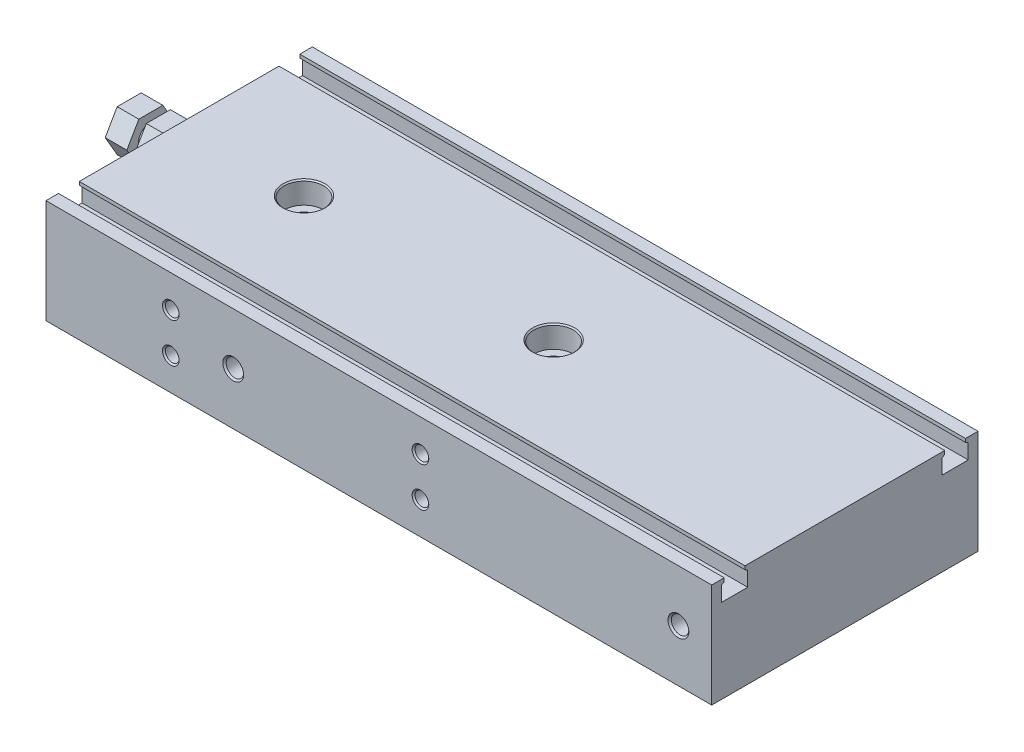
SolidWorks part; units mm, degrees
ref_plane "Plane1" through (0, 0, 0) normal (0, 0, 1) x (1, 0, 0)
ref_plane "Plane2" through (0, 0, 0) normal (0, 1, 0) x (1, 0, 0)
ref_plane "Plane3" through (0, 0, 0) normal (1, 0, 0) x (0, 0, -1)
sketch "Body_Sketch" plane through (0, 0, 0) normal (1, 0, 0) x (0, 0, -1)
  line L0 (-32, 12.5) -> (-32, -12.5)
  line L1 (-32, -12.5) -> (32, -12.5)
  line L2 (32, -12.5) -> (32, 12.5)
  line L3 (32, 12.5) -> (-32, 12.5)
  line L4 (-25.3, 0) -> (25.3, 0) construction
  line L5 (0, -7.85) -> (0, 10.85) construction
  line L6 (27.956, 0) -> (-27.956, 0) construction
  line L7 (0, 12.3416) -> (0, -12.3416) construction
  dimension "A" = 64
  dimension "B" = 25
  dimension "QQ" = 12.5
extrude "Body" add sketch "Body_Sketch" along normal blind 160
sketch "Body Bot Grooves_Sketch" [suppressed] plane through (0, 0, 0) normal (1, 0, 0) x (0, 0, -1)
  line L0 (0, 0) -> (0, -14.4793) construction
  line L1 (-12, -6.5) -> (-4, -6.5)
  line L2 (-4, -6.5) -> (-5, -5.5)
  line L3 (-5, -5.5) -> (-11, -5.5)
  line L4 (-11, -5.5) -> (-12, -6.5)
  line L5 (-8, -5.5) -> (-8, -12.5787) construction
  line L6 (18.5, 10) -> (-18.5, 10) construction
  line L7 (11, -5.5) -> (12, -6.5)
  line L8 (5, -5.5) -> (11, -5.5)
  line L9 (4, -6.5) -> (5, -5.5)
  line L10 (12, -6.5) -> (4, -6.5)
  dimension "Angle" = 45
  dimension "Raw Height" = 16.5
  dimension "Loc Y" = 15.5
  dimension "Width" = 8
  dimension "C2C" = 16
extrude "Body Bot Grooves" [suppressed] cut sketch "Body Bot Grooves_Sketch" along normal through all
sketch "Body Rod Holes_Sketch" plane through (0, 0, 0) normal (-1, 0, 0) x (0, 0, 1)
  line L0 (27.956, 0) -> (-27.956, 0) construction
  line L1 (0, 11.1009) -> (0, -8.2638) construction
  line L2 (0, -12.3416) -> (0, 12.3416) construction
  circle A0 centre (-14, 0) radius 5
  circle A1 centre (14, 0) radius 5
  dimension "NN" = 10
  dimension "H" = 28
extrude "Body Rod Holes" cut sketch "Body Rod Holes_Sketch" against normal blind 10
sketch "Body Piston Holes_Sketch" plane through (10, 0, 0) normal (-1, 0, 0) x (0, 0, 1)
  circle A0 centre (14, 0) radius 6.05
  circle A1 centre (-14, 0) radius 6.05
extrude "Body Piston Holes" cut sketch "Body Piston Holes_Sketch" against normal blind 91
sketch "Body Thru Hole_Sketch" [suppressed] plane through (0, 0, 0) normal (1, 0, 0) x (0, 0, -1)
  line L0 (0, 0) -> (0, -9.4152) construction
  line L1 (11.5, -6) -> (18.5, -6) construction
  circle A0 centre (14.95, -3) radius 1.4
  dimension "Dia" = 2.8
  dimension "Loc Y" = 3
  dimension "Loc Z" = 14.95
extrude "Body Thru Hole" [suppressed] cut sketch "Body Thru Hole_Sketch" along normal through all
sketch "Bot Switch Groove_Sketch" [suppressed] plane through (0, 0, 0) normal (1, 0, 0) x (0, 0, -1)
  line L0 (0, 0) -> (0, -12.0384) construction
  line L1 (1.6, -6.5) -> (-1.6, -6.5)
  line L2 (-1.6, -6.5) -> (-1.6, -3)
  line L3 (-1.6, -3) -> (-2.8, -3)
  line L4 (-2.8, -3) -> (-2.8, 0)
  line L5 (-2.8, 0) -> (2.8, 0)
  line L6 (2.8, -3) -> (2.8, 0)
  line L7 (-12, -6.5) -> (-4, -6.5) construction
  line L8 (1.6, -3) -> (2.8, -3)
  line L10 (1.6, -6.5) -> (1.6, -3)
  point P12 (0, 0)
  point P15 (0, -6.5)
  dimension "Bot Height" = 3.5
  dimension "Top Height" = 3
  dimension "Bot Width" = 3.2
  dimension "Top Width" = 5.6
extrude "Bot Switch Groove" [suppressed] cut sketch "Bot Switch Groove_Sketch" along normal through all
sketch "Top Switch Grooves_Sketch" plane through (0, 0, 0) normal (-1, 0, 0) x (0, 0, 1)
  line L0 (0, -12.3416) -> (0, 12.3416) construction
  line L1 (26.5, 4.6906) -> (26.5, 11.0706) construction
  line L2 (-32, 12.5) -> (32, 12.5) construction
  line L3 (23.35, 7.7) -> (29.65, 7.7)
  line L4 (-23.35, 11.3) -> (-23.35, 7.7)
  line L5 (-23.35, 7.7) -> (-29.65, 7.7)
  line L6 (-29.65, 7.7) -> (-29.65, 11.3)
  line L7 (-29, 12.5) -> (-24, 12.5)
  line L8 (29.65, 7.7) -> (29.65, 11.3)
  line L9 (29, 11.6753) -> (29.65, 11.3)
  line L10 (29, 12.5) -> (29, 11.6753)
  line L11 (29, 12.5) -> (24, 12.5)
  line L12 (-29, 12.5) -> (-29, 11.6753)
  line L13 (-24, 12.5) -> (-24, 11.6753)
  line L14 (-24, 11.6753) -> (-23.35, 11.3)
  line L15 (-29, 11.6753) -> (-29.65, 11.3)
  line L16 (0, 4.91) -> (0, 11.29) construction
  line L17 (24, 12.5) -> (24, 11.6753)
  line L18 (-26.5, 4.91) -> (-26.5, 11.29) construction
  line L19 (24, 11.6753) -> (23.35, 11.3)
  line L20 (23.35, 11.3) -> (23.35, 7.7)
  point P4 (-26.5, 12.5)
  point P12 (26.5, 12.5)
  dimension "Bot Width" = 6.3
  dimension "Top Width" = 5
  dimension "P" = 53
  dimension "Bot Height" = 3.6
  dimension "Angle" = 120
  dimension "Depth" = 4.8
extrude "Top Switch Grooves" cut sketch "Top Switch Grooves_Sketch" against normal through all
sketch "SHCS MGT Hole_Sketch" plane through (0, 0, 0) normal (0, 0, 1) x (1, 0, 0)
  line L0 (30, 12.5) -> (25.25, 12.5)
  line L1 (25.25, 12.5) -> (25.25, 7.2)
  line L2 (25.25, 7.2) -> (27.25, 7.2)
  line L3 (27.25, 7.2) -> (27.25, -12.5)
  line L4 (27.25, -12.5) -> (30, -12.5)
  line L5 (30, -12.5) -> (30, 12.5)
  line L6 (30, -11.5069) -> (30, 12.6548) construction
  line L7 (160, 12.5) -> (0, 12.5) construction
  line L8 (160, -12.5) -> (0, -12.5) construction
  line L9 (0, -12.5712) -> (0, 12.5712) construction
  dimension "M_depth" = 5.3
  dimension "M" = 9.5
  dimension "U" = 5.5
  dimension "L" = 30
revolve "SHCS MGT Hole" cut sketch "SHCS MGT Hole_Sketch" angle 360 about L6
chamfer "SHCS MGT Hole Cham" distance 0.3 1 edges at (30, 12.5, -4.75)
pattern_linear "SHCS MGT Hole Pat" count 2 spacing 60 along (1, 0, 0) of "SHCS MGT Hole", "SHCS MGT Hole Cham"
hole_wizard "SHCS MGT Hole Bot Tap" positions "SHCS MGT Hole Bot Tap Loc" profile "SHCS MGT Hole Bot Tap Profile" tap size "M4x0.7" standard "Ansi Metric"
sketch "SHCS MGT Hole Bot Tap Loc" plane through (0, -12.5, 0) normal (0, -1, 0) x (1, 0, 0)
  circle A0 centre (90, 0) radius 2.75 construction
  circle A1 centre (30, 0) radius 2.75 construction
  point P0 (30, 0)
  point P1 (90, 0)
sketch "SHCS MGT Hole Bot Tap Profile" plane through (30, -12.5, 0) normal (1, 0, 0) x (0, 0, -1)
  line L0 (0, 0) -> (0, 12.6524)
  line L1 (0, 12.6524) -> (2.75, 11)
  line L2 (2.75, 11) -> (2.75, 10)
  line L3 (2.75, 10) -> (3, 10)
  line L5 (3, 10) -> (3, 0.3)
  line L6 (3, 0.3) -> (3.3, 0)
  line L7 (3.3, 0) -> (0, 0)
  line L8 (-3, 0.3) -> (-3.3, 0) construction
  line L10 (0, 12.6524) -> (-2.75, 11) construction
  line L11 (0, -6.35) -> (0, 107.95) construction
  dimension "Tap Drill Dia." = 5.5
  dimension "Tap Drill Depth" = 11
  dimension "Thread Major Dia." = 6
  dimension "Thread Depth" = 10
  dimension "Near CSink Dia." = 6.6
  dimension "Near CSink Angle" = 90
  dimension "Drill Angle" = 118
sketch "Adjuster Nut_Sketch" plane through (0, 0, 0) normal (-1, 0, 0) x (0, 0, 1)
  line L0 (-2.8868, 11.5) -> (2.8868, 11.5)
  line L1 (2.8868, 11.5) -> (5.7735, 6.5)
  line L2 (2.8868, 1.5) -> (5.7735, 6.5)
  line L3 (2.8868, 1.5) -> (-2.8868, 1.5)
  line L4 (-5.7735, 6.5) -> (-2.8868, 1.5)
  line L5 (-2.8868, 11.5) -> (-5.7735, 6.5)
  line L6 (0, -12.3416) -> (0, 12.3416) construction
  line L7 (27.956, 0) -> (-27.956, 0) construction
  line L8 (-4.4456, 6.5) -> (4.4456, 6.5) construction
  line L10 (0, 1.15) -> (0, 8.85) construction
  circle A0 centre (0, 6.5) radius 5 construction
  dimension "OO_keyw" = 10
  dimension "TT" = 6.5
extrude "Adjuster Nut" add sketch "Adjuster Nut_Sketch" along normal blind 12
sketch "Adjuster Nut Threads_Sketch" plane through (0, 0, 0) normal (0, 0, 1) x (1, 0, 0)
  line L0 (-6.8, 34.5) -> (-6.8, 9.5)
  line L1 (-6.8, 9.5) -> (-5, 9.5)
  line L2 (-5, 9.5) -> (-5, 34.5)
  line L3 (-5, 34.5) -> (-6.8, 34.5)
  line L4 (-6.476, 6.5) -> (-3.044, 6.5) construction
  line L5 (-12, 6.5) -> (0, 6.5) construction
  line L6 (0, -12.5712) -> (0, 12.5712) construction
  line L7 (-12, 6.5) -> (-12, 11.5) construction
  line L8 (0, 12.5) -> (0, -12.5) construction
  dimension "OO" = 6
  dimension "Nut Thickness Body" = 5
  dimension "Nut Thickness Plate" = 5.2
revolve "Adjuster Nut Threads" cut sketch "Adjuster Nut Threads_Sketch" angle 360 about L4
hole_wizard "Tap Drill for M5x0.8 Tap1" positions "Sketch2" profile "Sketch1" hole size "M5x0.8" standard "ANSI Metric"
sketch "Sketch2" plane through (0, 0, 32) normal (0, 0, 1) x (1, 0, 0)
  line L0 (160, -12.5) -> (0, -12.5) construction
  line L1 (160, 12.5) -> (160, -12.5) construction
  line L2 (0, 12.5) -> (0, -12.5) construction
  point P0 (45, 0)
  point P2 (152, 0)
  dimension "D1" = 12.5
  dimension "D2" = 8
  dimension "D3" = 45
sketch "Sketch1" plane through (45, 0, 32) normal (1, 0, 0) x (0, -1, 0)
  line L0 (0, 0) -> (0, 5.7618)
  line L1 (0, 5.7618) -> (2.1, 4.5)
  line L2 (2.1, 4.5) -> (2.1, 0.4)
  line L3 (2.1, 0.4) -> (2.5, 0)
  line L5 (2.5, 0) -> (0, 0)
  line L6 (-2.1, 0.4) -> (-2.5, 0) construction
  line L10 (0, 5.7618) -> (-2.1, 4.5) construction
  line L11 (0, -6.35) -> (0, 107.95) construction
  dimension "Hole Dia." = 4.2
  dimension "Hole Depth" = 4.5
  dimension "Near C'Sink Dia." = 5
  dimension "Near C'Sink Angle" = 90
  dimension "Drill Angle" = 118
hole_wizard "Tap Drill for M5x0.8 Tap2" positions "Sketch4" profile "Sketch3" hole size "M5x0.8" standard "ANSI Metric"
sketch "Sketch4" plane through (0, 0, -32) normal (0, 0, -1) x (-1, 0, 0)
  line L0 (-160, -12.5) -> (-160, 12.5) construction
  line L1 (0, -12.5) -> (0, 12.5) construction
  line L2 (-160, -12.5) -> (0, -12.5) construction
  point P0 (-152, 0)
  point P2 (-45, 0)
  dimension "D1" = 8
  dimension "D2" = 45
  dimension "D3" = 12.5
sketch "Sketch3" plane through (152, 0, -32) normal (1, 0, 0) x (0, 1, 0)
  line L0 (0, 0) -> (0, 5.7618)
  line L1 (0, 5.7618) -> (2.1, 4.5)
  line L2 (2.1, 4.5) -> (2.1, 0.4)
  line L3 (2.1, 0.4) -> (2.5, 0)
  line L5 (2.5, 0) -> (0, 0)
  line L6 (-2.1, 0.4) -> (-2.5, 0) construction
  line L10 (0, 5.7618) -> (-2.1, 4.5) construction
  line L11 (0, -6.35) -> (0, 107.95) construction
  dimension "Hole Dia." = 4.2
  dimension "Hole Depth" = 4.5
  dimension "Near C'Sink Dia." = 5
  dimension "Near C'Sink Angle" = 90
  dimension "Drill Angle" = 118
hole_wizard "Mount_Holes_1" positions "Sketch6" profile "Sketch5" hole size "M3x0.5" standard "ANSI Metric"
sketch "Sketch6" plane through (0, 0, 32) normal (0, 0, 1) x (1, 0, 0)
  line L0 (160, -12.5) -> (0, -12.5) construction
  line L1 (0, 12.5) -> (0, -12.5) construction
  point P0 (30, -4.75)
  point P2 (90, -4.75)
  dimension "D1" = 7.75
  dimension "D2" = 30
  dimension "D3" = 60
sketch "Sketch5" plane through (30, -4.75, 32) normal (1, 0, 0) x (0, -1, 0)
  line L0 (0, 0) -> (0, 6.4914)
  line L1 (0, 6.4914) -> (1.65, 5.5)
  line L2 (1.65, 5.5) -> (1.65, 0.35)
  line L3 (1.65, 0.35) -> (2, 0)
  line L5 (2, 0) -> (0, 0)
  line L6 (-1.65, 0.35) -> (-2, 0) construction
  line L10 (0, 6.4914) -> (-1.65, 5.5) construction
  line L11 (0, -6.35) -> (0, 107.95) construction
  dimension "Hole Dia." = 3.3
  dimension "Hole Depth" = 5.5
  dimension "Near C'Sink Dia." = 4
  dimension "Near C'Sink Angle" = 90
  dimension "Drill Angle" = 118
hole_wizard "Mount_Holes_2" positions "Sketch8" profile "Sketch7" hole size "M3x0.5" standard "ANSI Metric"
sketch "Sketch8" plane through (0, 0, -32) normal (0, 0, -1) x (-1, 0, 0)
  line L0 (-160, -12.5) -> (0, -12.5) construction
  line L1 (0, -12.5) -> (0, 12.5) construction
  point P0 (-90, -4.75)
  point P2 (-30, -4.75)
  dimension "D1" = 7.75
  dimension "D2" = 30
  dimension "D3" = 60
sketch "Sketch7" plane through (90, -4.75, -32) normal (1, 0, 0) x (0, 1, 0)
  line L0 (0, 0) -> (0, 6.4914)
  line L1 (0, 6.4914) -> (1.65, 5.5)
  line L2 (1.65, 5.5) -> (1.65, 0.35)
  line L3 (1.65, 0.35) -> (2, 0)
  line L5 (2, 0) -> (0, 0)
  line L6 (-1.65, 0.35) -> (-2, 0) construction
  line L10 (0, 6.4914) -> (-1.65, 5.5) construction
  line L11 (0, -6.35) -> (0, 107.95) construction
  dimension "Hole Dia." = 3.3
  dimension "Hole Depth" = 5.5
  dimension "Near C'Sink Dia." = 4
  dimension "Near C'Sink Angle" = 90
  dimension "Drill Angle" = 118
hole_wizard "Mount_Holes_3" positions "Sketch10" profile "Sketch9" hole size "M4x0.7" standard "ANSI Metric"
sketch "Sketch10" plane through (0, 0, 32) normal (0, 0, 1) x (1, 0, 0)
  line L0 (160, 12.5) -> (0, 12.5) construction
  line L1 (0, 12.5) -> (0, -12.5) construction
  point P0 (30, 4.75)
  point P2 (90, 4.75)
  dimension "D1" = 7.75
  dimension "D2" = 30
  dimension "D3" = 60
sketch "Sketch9" plane through (30, 4.75, 32) normal (1, 0, 0) x (0, -1, 0)
  line L0 (0, 0) -> (0, 6.4914)
  line L1 (0, 6.4914) -> (1.65, 5.5)
  line L2 (1.65, 5.5) -> (1.65, 0.35)
  line L3 (1.65, 0.35) -> (2, 0)
  line L5 (2, 0) -> (0, 0)
  line L6 (-1.65, 0.35) -> (-2, 0) construction
  line L10 (0, 6.4914) -> (-1.65, 5.5) construction
  line L11 (0, -6.35) -> (0, 107.95) construction
  dimension "Hole Dia." = 3.3
  dimension "Hole Depth" = 5.5
  dimension "Near C'Sink Dia." = 4
  dimension "Near C'Sink Angle" = 90
  dimension "Drill Angle" = 118
hole_wizard "Mount_Holes_4" positions "Sketch12" profile "Sketch11" hole size "M4x0.7" standard "ANSI Metric"
sketch "Sketch12" plane through (0, 0, -32) normal (0, 0, -1) x (-1, 0, 0)
  line L1 (-160, 12.5) -> (0, 12.5) construction
  line L2 (0, -12.5) -> (0, 12.5) construction
  point P0 (-90, 4.75)
  point P2 (-30, 4.75)
  dimension "D1" = 7.75
  dimension "D2" = 30
  dimension "D3" = 60
sketch "Sketch11" plane through (90, 4.75, -32) normal (1, 0, 0) x (0, 1, 0)
  line L0 (0, 0) -> (0, 6.4914)
  line L1 (0, 6.4914) -> (1.65, 5.5)
  line L2 (1.65, 5.5) -> (1.65, 0.35)
  line L3 (1.65, 0.35) -> (2, 0)
  line L5 (2, 0) -> (0, 0)
  line L6 (-1.65, 0.35) -> (-2, 0) construction
  line L10 (0, 6.4914) -> (-1.65, 5.5) construction
  line L11 (0, -6.35) -> (0, 107.95) construction
  dimension "Hole Dia." = 3.3
  dimension "Hole Depth" = 5.5
  dimension "Near C'Sink Dia." = 4
  dimension "Near C'Sink Angle" = 90
  dimension "Drill Angle" = 118
hole_wizard "1/8 Rc Tapped Hole1" positions "Sketch14" profile "Sketch13" size "1/8" standard "ISO"
sketch "Sketch14" plane through (0, 0, 49) normal (0, 0, 1) x (1, 0, 0)
  line L0 (182, -19) -> (0, -19) construction
  line L1 (0, 19) -> (0, -19) construction
  line L2 (182, 19) -> (182, -19) construction
  point P0 (56, 0)
  point P2 (172, 0)
  dimension "D1" = 15
  dimension "D2" = 46
  dimension "D3" = 9
sketch "Sketch13" plane through (56, 0, 49) normal (1, 0, 0) x (0, -1, 0)
  line L0 (0, 0) -> (0, 11.4134)
  line L1 (3.95, 9.04) -> (0, 11.4134)
  line L2 (-3.95, 9.04) -> (0, 11.4134) construction
  line L3 (3.95, 9.04) -> (3.95, 4.5)
  line L4 (3.95, 4.5) -> (4.633, 4.5)
  line L5 (4.633, 4.5) -> (4.7735, 0)
  line L6 (-4.633, 4.5) -> (-4.7735, 0) construction
  line L7 (4.7735, 0) -> (0, 0)
  line L8 (0, -6.35) -> (0, 107.95) construction
  line L11 (-3.95, 4.5) -> (-4.633, 4.5) construction
  dimension "Tap Drill Dia." = 7.9
  dimension "Tap Drill Depth" = 9.04
  dimension "Thread Dia." = 9.5469
  dimension "Thread Angle" = 3.576
  dimension "Thread Depth" = 4.5
  dimension "Drill Angle" = 118
hole_wizard "1/8 Rc Tapped Hole2" positions "Sketch16" profile "Sketch15" size "1/8" standard "ISO"
sketch "Sketch16" plane through (0, 0, -49) normal (0, 0, -1) x (-1, 0, 0)
  line L0 (-182, -19) -> (0, -19) construction
  line L1 (0, -19) -> (0, 19) construction
  line L2 (-182, -19) -> (-182, 19) construction
  point P0 (-172, 0)
  point P2 (-56, 0)
  dimension "D1" = 15
  dimension "D2" = 46
  dimension "D3" = 9
sketch "Sketch15" plane through (172, 0, -49) normal (1, 0, 0) x (0, 1, 0)
  line L0 (0, 0) -> (0, 11.4134)
  line L1 (3.95, 9.04) -> (0, 11.4134)
  line L2 (-3.95, 9.04) -> (0, 11.4134) construction
  line L3 (3.95, 9.04) -> (3.95, 4.5)
  line L4 (3.95, 4.5) -> (4.633, 4.5)
  line L5 (4.633, 4.5) -> (4.7735, 0)
  line L6 (-4.633, 4.5) -> (-4.7735, 0) construction
  line L7 (4.7735, 0) -> (0, 0)
  line L8 (0, -6.35) -> (0, 107.95) construction
  line L11 (-3.95, 4.5) -> (-4.633, 4.5) construction
  dimension "Tap Drill Dia." = 7.9
  dimension "Tap Drill Depth" = 9.04
  dimension "Thread Dia." = 9.5469
  dimension "Thread Angle" = 3.576
  dimension "Thread Depth" = 4.5
  dimension "Drill Angle" = 118
